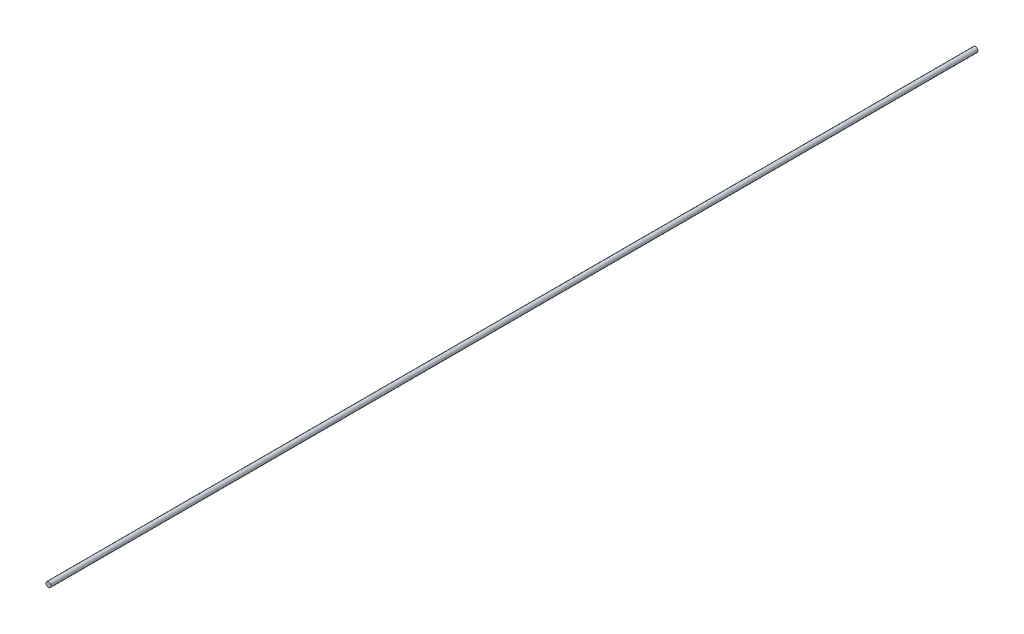
SolidWorks part; units mm, degrees
material "7075-T6, Plate (SS)"
ref_plane "Front Plane" through (0, 0, 0) normal (0, 0, 1) x (1, 0, 0)
ref_plane "Top Plane" through (0, 0, 0) normal (0, 1, 0) x (1, 0, 0)
ref_plane "Right Plane" through (0, 0, 0) normal (1, 0, 0) x (0, 0, -1)
sketch "Sketch1" plane through (0, 0, 0) normal (0, 0, 1) x (1, 0, 0)
  circle A0 centre (0, 0) radius 12.7
  dimension "D1" = 25.4
extrude "Boss-Extrude1" add sketch "Sketch1" along normal blind 4684.89
equation "\"Diameter\" = 1"
equation "\"Length\"= \"Deflection\" * \"Elastic Modoulous\" * \"Cross Sectional Area\" / \"Force (LBS)\""
equation "\"Cross Sectional Area\"= 3.14 * ( \"Diameter\" / 2 ) ^ 2"
equation "\"Deflection\"= .009"
equation "\"Elastic Modoulous\"= 10442717"
equation "\"Force (LBS)\"= 400"
equation "\"D1@Sketch1\"=\"Diameter\""
equation "\"D1@Boss-Extrude1\"=\"Length\""
